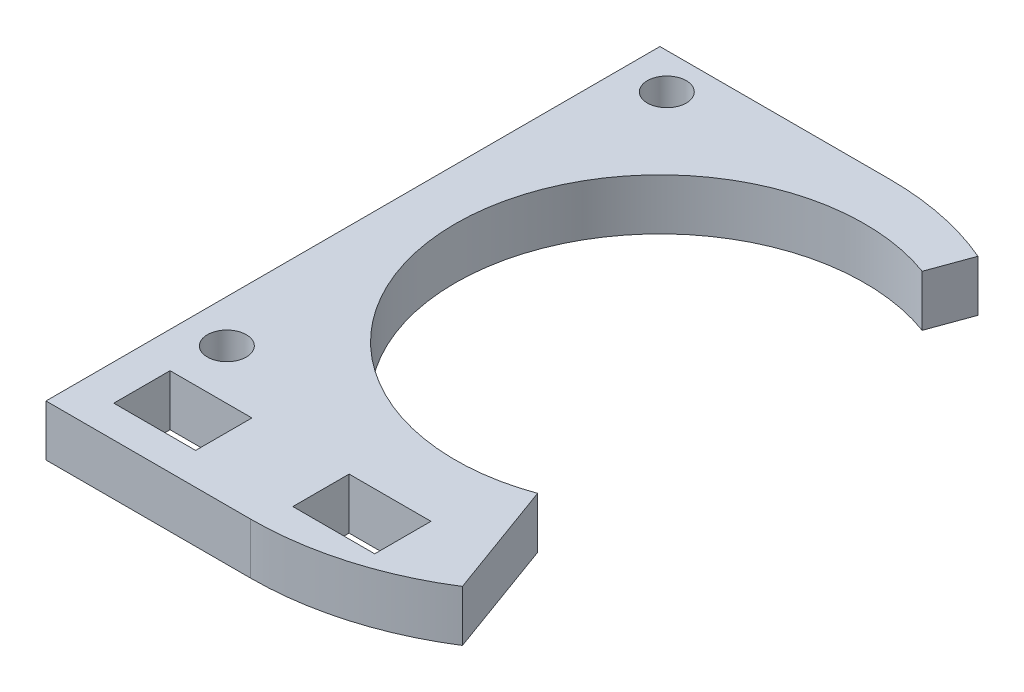
SolidWorks part; units mm, degrees
ref_plane "Front" through (0, 0, 0) normal (0, 0, 1) x (1, 0, 0)
ref_plane "Top" through (0, 0, 0) normal (0, 1, 0) x (1, 0, 0)
ref_plane "Right" through (0, 0, 0) normal (1, 0, 0) x (0, 0, -1)
sketch "Croquis1" plane through (0, 0, 0) normal (0, 1, 0) x (1, 0, 0)
  line L0 (-356.9204, 0) -> (17489.0978, 0) construction
  line L1 (0, -356.9204) -> (0, 17489.0978) construction
  line L2 (10, -986.0798) -> (10, 49013.9202) construction
  line L3 (0, 0) -> (8, 0)
  line L4 (0, 0) -> (0, 24)
  line L5 (0, 24) -> (9, 24)
  line L6 (20, 12) -> (20, 13)
  line L7 (-697.1068, -693.1068) -> (34658.2323, 34662.2323) construction
  line L8 (8.4, 3.45) -> (11.6, 3.45)
  line L9 (8.4, 3.45) -> (8.4, 1.25)
  line L10 (8.4, 1.25) -> (11.6, 1.25)
  line L11 (11.6, 3.45) -> (11.6, 1.25)
  line L12 (8.4, 3.45) -> (11.6, 1.25) construction
  line L13 (8.4, 1.25) -> (11.6, 3.45) construction
  line L14 (-685.9891, 732.5482) -> (34101.0787, -35182.0716) construction
  line L15 (-990, 14) -> (49010, 14) construction
  line L16 (6.5, -986.0798) -> (6.5, 49013.9202) construction
  line L17 (4.6, 3.45) -> (4.6, 1.25)
  line L18 (4.6, 1.25) -> (1.4, 1.25)
  line L19 (1.4, 3.45) -> (1.4, 1.25)
  line L20 (4.6, 3.45) -> (1.4, 3.45)
  circle A0 centre (10, 14) radius 8
  circle A1 centre (1.67, 22.6) radius 0.76
  circle A2 centre (1.67, 5.4) radius 0.76
  arc A3 (20, 13) -> (9, 24) centre (9, 13) ccw
  arc A4 (20, 12) -> (8, 0) centre (8, 12) cw
  point P9 (10, 2.35)
  dimension "D1" = 16
  dimension "D3" = 10
  dimension "D5" = 10
  dimension "D9" = 1.52
  dimension "D10" = 1.67
  dimension "D11" = 1.4
  dimension "D12" = 11
  dimension "D13" = 12
  dimension "D14" = 3.5
  dimension "D2" = 14
  dimension "D4" = 24
  dimension "D6" = 3.2
  dimension "D7" = 2.2
  dimension "D8" = 1.25
extrude "Saliente-Extruir1" add sketch "Croquis1" along normal blind 2
sketch "Croquis2" plane through (0, 2, 0) normal (0, 1, 0) x (1, 0, 0)
  line L0 (10, -986) -> (10, 49014) construction
  line L1 (-990, 14) -> (49010, 14) construction
  line L2 (-332.0201, -925.6926) -> (16768.987, 46058.9384) construction
  line L3 (-320.3661, 921.6734) -> (16780.6411, -46062.9577) construction
  line L4 (14.4183, 26.1393) -> (12.7362, 21.5175)
  line L5 (12.7362, 6.4825) -> (14.4183, 1.8607)
  circle A0 centre (10, 14) radius 8 construction
  arc A1 (12.7362, 21.5175) -> (12.7362, 6.4825) centre (10, 14) cw
  arc A2 (14.4183, 1.8607) -> (14.4183, 26.1393) centre (10, 14) ccw
  arc A3 (8, 0) -> (20, 12) centre (8, 12) ccw construction
extrude "Cortar-Extruir1" cut sketch "Croquis2" against normal blind 10
sketch "Croquis3" plane through (0, 0, 0) normal (0, 1, 0) x (1, 0, 0)
  line L1 (0, 24) -> (9, 24)
  line L2 (0, 24) -> (0, 25.5)
  line L3 (0, 25.5) -> (9, 25.5)
  line L4 (9, 24) -> (9, 25.5)
  dimension "D1" = 9
  dimension "D2" = 1.5
extrude "Saliente-Extruir2" [suppressed] add sketch "Croquis3" along normal blind 4
